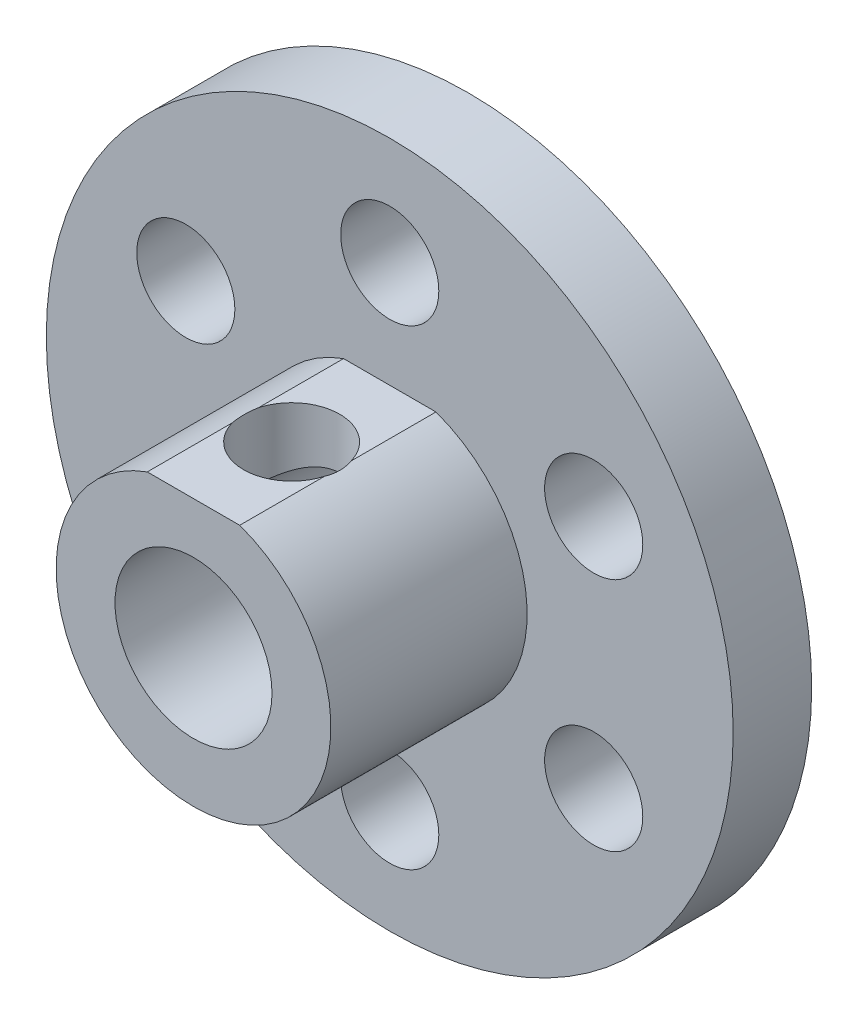
SolidWorks part; units mm, degrees
ref_plane "Front Plane" through (0, 0, 0) normal (0, 0, 1) x (1, 0, 0)
ref_plane "Top Plane" through (0, 0, 0) normal (0, 1, 0) x (1, 0, 0)
ref_plane "Right Plane" through (0, 0, 0) normal (1, 0, 0) x (0, 0, -1)
sketch "Sketch1" plane through (0, 0, 0) normal (0, 0, 1) x (1, 0, 0)
  circle A0 centre (0, 0) radius 17.5
  circle A1 centre (0, 12) radius 2.5
  circle A2 centre (10.3923, 6) radius 2.5
  circle A3 centre (10.3923, -6) radius 2.5
  circle A4 centre (0, -12) radius 2.5
  circle A5 centre (-10.3923, -6) radius 2.5
  circle A6 centre (-10.3923, 6) radius 2.5
  circle A7 centre (0, 0) radius 4
  point P18 (0, 0)
  dimension "D1" = 35
  dimension "D2" = 5
  dimension "D5" = 8
  dimension "D3" = 12
  dimension "D4" = 6
extrude "Boss-Extrude1" add sketch "Sketch1" along normal blind 4
sketch "Sketch3" plane through (0, 0, 4) normal (0, 0, 1) x (1, 0, 0)
  line L1 (2.3551, 6.5919) -> (-2.3551, 6.5919)
  arc A0 (-2.3551, 6.5919) -> (2.3551, 6.5919) centre (0, 0) ccw
  circle A1 centre (0, 0) radius 4
  circle A2 centre (0, 0) radius 17.5 construction
  point P1 (-2.992, 6.3284)
  point P5 (-2.3551, 6.5919)
  dimension "D1" = 14
  dimension "D2" = 8
extrude "Boss-Extrude2" add sketch "Sketch3" along normal blind 10
sketch "Sketch4" plane through (0, 6.5919, 0) normal (0, 1, 0) x (1, 0, 0)
  line L0 (0, -9) -> (0, -4) construction
  line L1 (2.3551, -4) -> (-2.3551, -4) construction
  line L2 (0, -9) -> (0, -14) construction
  line L3 (2.3551, -14) -> (-2.3551, -14) construction
  circle A0 centre (0, -9) radius 2.45
  dimension "D1" = 4.9
extrude "Cut-Extrude1" cut sketch "Sketch4" against normal blind 4 contours A0
